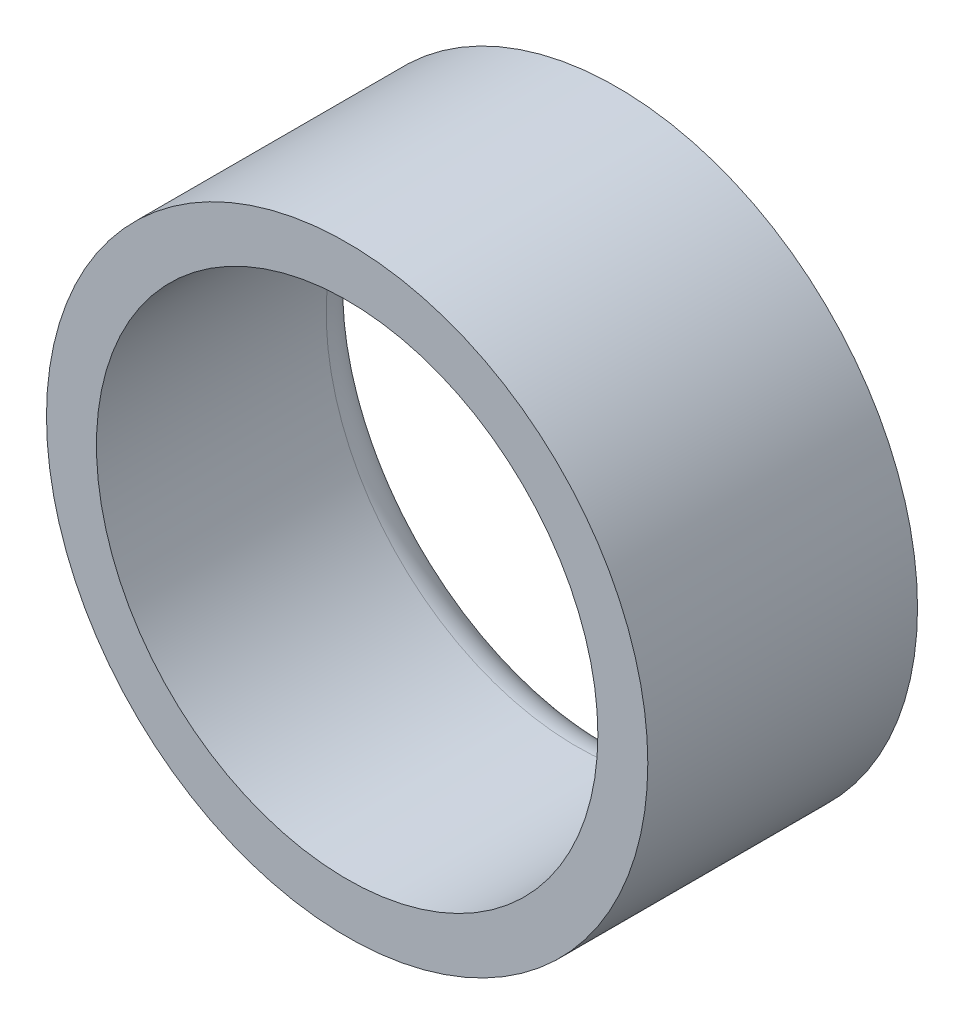
SolidWorks part; units mm, degrees
ref_plane "Front Plane" through (0, 0, 0) normal (0, 0, 1) x (1, 0, 0)
ref_plane "Top Plane" through (0, 0, 0) normal (0, 1, 0) x (1, 0, 0)
ref_plane "Right Plane" through (0, 0, 0) normal (1, 0, 0) x (0, 0, -1)
sketch "Sketch1" plane through (0, 0, 0) normal (0, 0, 1) x (1, 0, 0)
  circle A1 centre (0, 0) radius 15.9385
  circle A2 centre (0, 0) radius 19.1135
  dimension "D1" = 31.877
  dimension "D2" = 38.227
extrude "Boss-Extrude1" add sketch "Sketch1" along normal blind 17.145
fillet "Fillet1" radius 2.54 1 edges at (15.9385, 0, 0)
